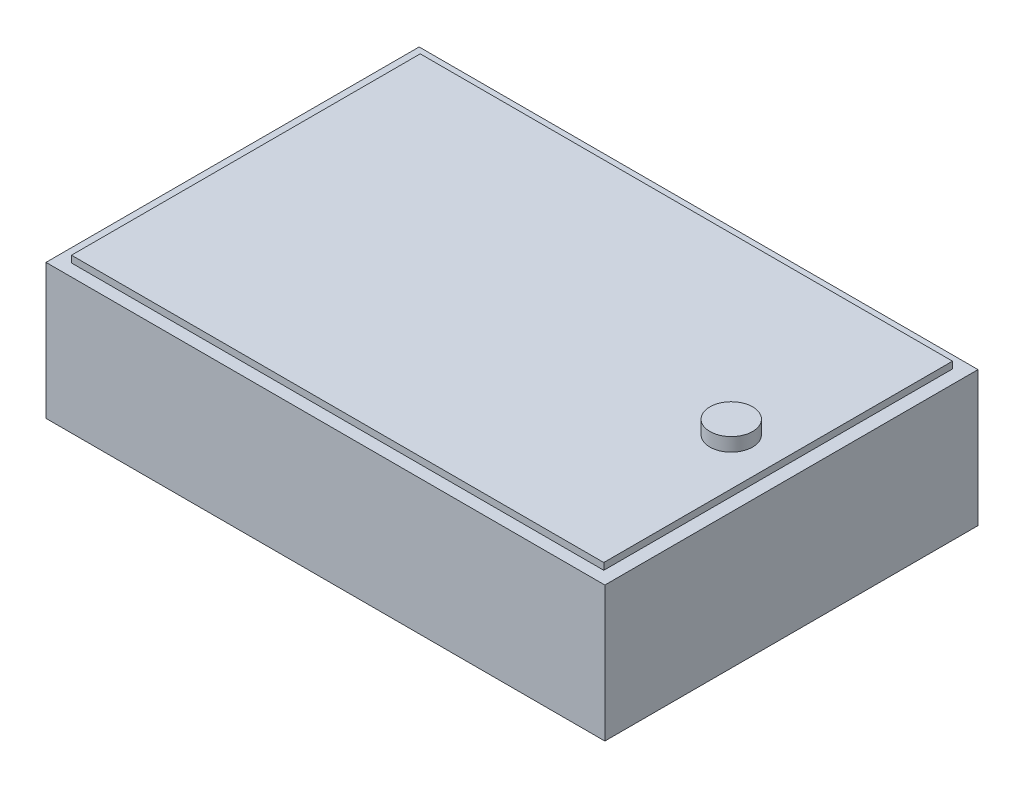
SolidWorks part; units mm, degrees
ref_plane "Front Plane" through (0, 0, 0) normal (0, 0, 1) x (1, 0, 0)
ref_plane "Top Plane" through (0, 0, 0) normal (0, 1, 0) x (1, 0, 0)
ref_plane "Right Plane" through (0, 0, 0) normal (1, 0, 0) x (0, 0, -1)
sketch "Sketch1" plane through (0, 0, 0) normal (0, 1, 0) x (1, 0, 0)
  line L1 (-124.0587, 82.8319) -> (124.0587, 82.8319)
  line L2 (-124.0587, 82.8319) -> (-124.0587, -82.8319)
  line L3 (-124.0587, -82.8319) -> (124.0587, -82.8319)
  line L4 (124.0587, 82.8319) -> (124.0587, -82.8319)
  line L5 (-124.0587, 82.8319) -> (124.0587, -82.8319) construction
  line L6 (-124.0587, -82.8319) -> (124.0587, 82.8319) construction
  point P0 (0, 0)
extrude "Boss-Extrude1" add sketch "Sketch1" along normal blind 60
sketch "Sketch2" plane through (0, 60, 0) normal (0, 1, 0) x (1, 0, 0)
  line L1 (-118.1582, 77.414) -> (118.1582, 77.414)
  line L2 (-118.1582, 77.414) -> (-118.1582, -77.414)
  line L3 (-118.1582, -77.414) -> (118.1582, -77.414)
  line L4 (118.1582, 77.414) -> (118.1582, -77.414)
  line L5 (-118.1582, 77.414) -> (118.1582, -77.414) construction
  line L6 (-118.1582, -77.414) -> (118.1582, 77.414) construction
  point P0 (0, 0)
extrude "Boss-Extrude2" add sketch "Sketch2" along normal blind 3
sketch "Sketch3" plane through (0, 63, 0) normal (0, 1, 0) x (1, 0, 0)
  circle A0 centre (97.3433, 0) radius 9.4832
extrude "Boss-Extrude3" add sketch "Sketch3" along normal blind 6
sketch "Sketch4" plane through (0, 0, -82.8319) normal (0, 0, -1) x (-1, 0, 0)
  circle A0 centre (-83.9326, 31.205) radius 22.6988
  circle A1 centre (0, 31.205) radius 22.8205
  circle A2 centre (81.943, 31.205) radius 22.6988
extrude "Cut-Extrude1" cut sketch "Sketch4" against normal blind 15
